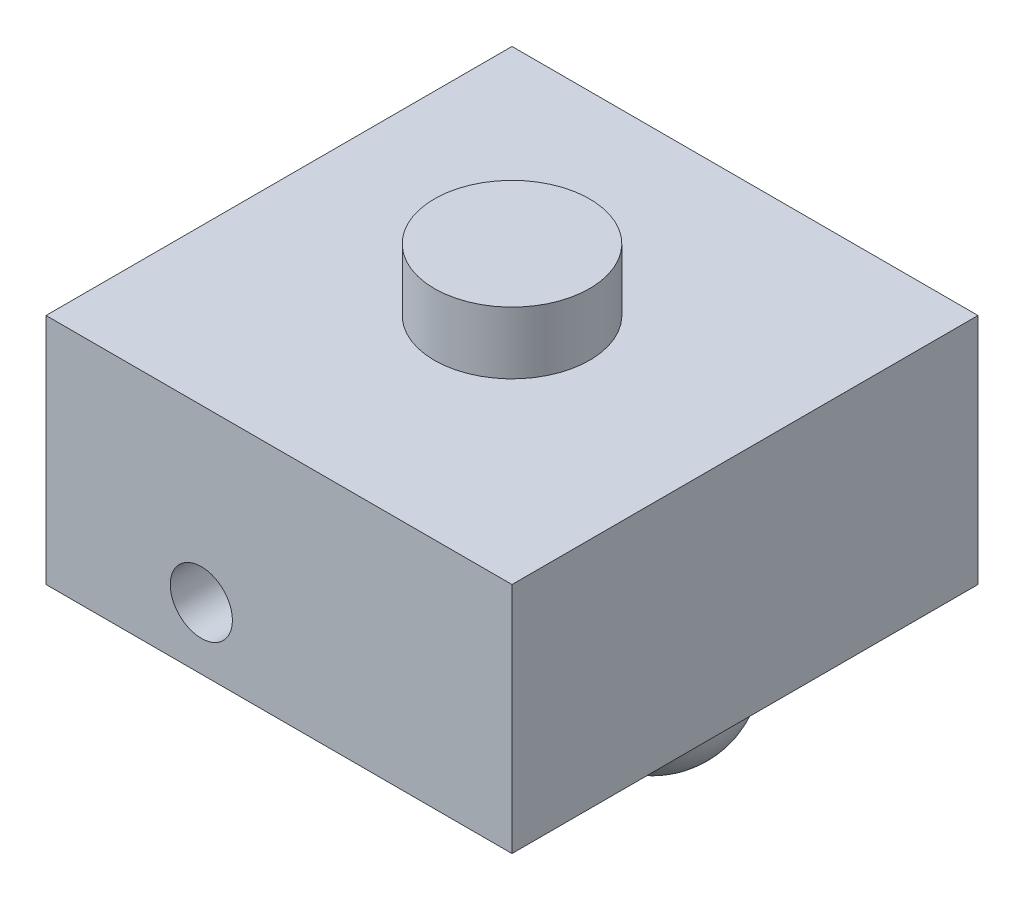
SolidWorks part; units mm, degrees
ref_plane "Front Plane" through (0, 0, 0) normal (0, 0, 1) x (1, 0, 0)
ref_plane "Top Plane" through (0, 0, 0) normal (0, 1, 0) x (1, 0, 0)
ref_plane "Right Plane" through (0, 0, 0) normal (1, 0, 0) x (0, 0, -1)
sketch "Sketch1" plane through (0, 0, 0) normal (0, 1, 0) x (1, 0, 0)
  line L1 (-150, 150) -> (150, 150)
  line L2 (-150, 150) -> (-150, -150)
  line L3 (-150, -150) -> (150, -150)
  line L4 (150, 150) -> (150, -150)
  line L5 (-150, 150) -> (150, -150) construction
  line L6 (-150, -150) -> (150, 150) construction
  point P0 (0, 0)
  dimension "D1" = 300
  dimension "D2" = 300
sketch "Sketch2" plane through (0, 0, 0) normal (0, 1, 0) x (1, 0, 0)
  line L0 (-150, 150) -> (150, 150)
  line L1 (-150, 150) -> (-150, -150)
  line L2 (-150, -150) -> (150, -150)
  line L3 (150, 150) -> (150, -150)
extrude "Boss-Extrude1" add sketch "Sketch2" along normal blind 150
sketch "Sketch3" plane through (0, 0, 150) normal (0, 0, 1) x (1, 0, 0)
  line L0 (-150, 40) -> (150, 40) construction
  line L1 (-150, 150) -> (-150, 0) construction
  line L2 (150, 150) -> (150, 0) construction
  line L3 (-150, 0) -> (150, 0) construction
  circle A0 centre (-50, 40) radius 20
  dimension "D3" = 40
  dimension "D1" = 40
  dimension "D2" = 100
sketch "Sketch4" plane through (0, 0, 150) normal (0, 0, 1) x (1, 0, 0)
  circle A0 centre (-50, 40) radius 20
extrude "Cut-Extrude1" cut sketch "Sketch4" against normal through all
sketch "Sketch8" plane through (0, 150, 0) normal (0, 1, 0) x (1, 0, 0)
  circle A0 centre (0, 0) radius 50
extrude "Boss-Extrude3" add sketch "Sketch8" along normal blind 40
sketch "Sketch9" plane through (0, 0, 0) normal (0, -1, 0) x (-1, 0, 0)
  line L0 (0, 0) -> (-180, 0) construction
  line L1 (-150, 150) -> (-150, -150) construction
  circle A0 centre (-90, 0) radius 50
  dimension "D1" = 100
  dimension "D2" = 60
sketch "Sketch10" plane through (0, 0, 0) normal (0, -1, 0) x (-1, 0, 0)
  circle A0 centre (-90, 0) radius 50
extrude "Boss-Extrude4" add sketch "Sketch10" along normal blind 50
fillet "Fillet1" radius 49 1 edges at (90, -50, -50)
